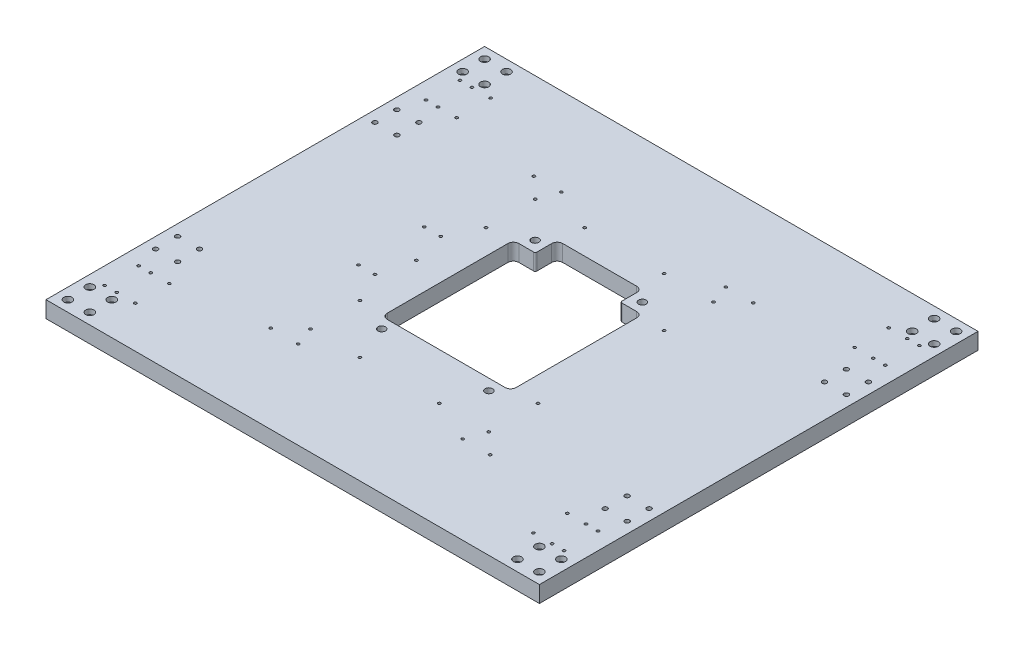
SolidWorks part; units mm, degrees
material "6061 Alloy"
ref_plane "Front Plane" through (0, 0, 0) normal (0, 0, 1) x (1, 0, 0)
ref_plane "Top Plane" through (0, 0, 0) normal (0, 1, 0) x (1, 0, 0)
ref_plane "Right Plane" through (0, 0, 0) normal (1, 0, 0) x (0, 0, -1)
sketch "Sketch2" plane through (0, 0, 0) normal (0, 1, 0) x (1, 0, 0)
  line L1 (-450, -400) -> (450, -400)
  line L2 (-450, -400) -> (-450, 400)
  line L3 (-450, 400) -> (450, 400)
  line L4 (450, -400) -> (450, 400)
  line L5 (-450, -400) -> (450, 400) construction
  line L6 (-450, 400) -> (450, -400) construction
  point P0 (0, 0)
  dimension "D1" = 800
  dimension "D2" = 900
extrude "Boss-Extrude1" add sketch "Sketch2" against normal blind 30
hole_wizard "M6 Tapped Hole1" positions "Sketch3" profile "Sketch4" tap size "M6" standard "GB"
sketch "Sketch3" plane through (0, 0, 0) normal (0, 1, 0) x (1, 0, 0)
  line L0 (-16.5, 0) -> (16.5, 0) construction
  line L1 (0, -16.5) -> (0, 16.5) construction
  line L2 (-174.35, -84) -> (-174.35, 84) construction
  point P0 (-419, 324.022)
  point P3 (-397, 324.022)
  point P6 (-363, 324.022)
  point P9 (-419, 262.022)
  point P12 (-397, 262.022)
  point P15 (-363, 262.022)
  point P27 (-200, 240)
  point P30 (-150, 240)
  point P33 (-162.5, 115)
  point P36 (-162.5, 205)
  point P39 (-72.5, 205)
  point P42 (-190.0019, 60)
  point P45 (-220.0019, 60)
  point P54 (-220.0019, -60)
  point P55 (-190.0019, -60)
  point P56 (-72.5, -205)
  point P57 (-162.5, -205)
  point P58 (-162.5, -115)
  point P59 (-150, -240)
  point P60 (-200, -240)
  point P61 (-363, -262.022)
  point P62 (-397, -262.022)
  point P63 (-419, -262.022)
  point P64 (-363, -324.022)
  point P65 (-397, -324.022)
  point P66 (-419, -324.022)
  point P69 (419, -324.022)
  point P70 (397, -324.022)
  point P71 (363, -324.022)
  point P72 (419, -262.022)
  point P73 (397, -262.022)
  point P74 (363, -262.022)
  point P75 (200, -240)
  point P76 (150, -240)
  point P77 (162.5, -115)
  point P78 (162.5, -205)
  point P79 (72.5, -205)
  point P84 (72.5, 205)
  point P85 (162.5, 205)
  point P86 (162.5, 115)
  point P87 (150, 240)
  point P88 (200, 240)
  point P89 (363, 262.022)
  point P90 (397, 262.022)
  point P91 (419, 262.022)
  point P92 (363, 324.022)
  point P93 (397, 324.022)
  point P94 (419, 324.022)
  point P95 (-174.35, 0)
cosmetic thread "Hole Thread1" parameters "D1"=20, "D2"=6
cosmetic thread "Hole Thread2" parameters "D1"=20, "D2"=6
cosmetic thread "Hole Thread3" parameters "D1"=20, "D2"=6
cosmetic thread "Hole Thread4" parameters "D1"=20, "D2"=6
cosmetic thread "Hole Thread5" parameters "D1"=20, "D2"=6
cosmetic thread "Hole Thread6" parameters "D1"=20, "D2"=6
cosmetic thread "Hole Thread7" parameters "D1"=20, "D2"=6
cosmetic thread "Hole Thread8" parameters "D1"=20, "D2"=6
cosmetic thread "Hole Thread9" parameters "D1"=20, "D2"=6
cosmetic thread "Hole Thread10" parameters "D1"=20, "D2"=6
cosmetic thread "Hole Thread11" parameters "D1"=20, "D2"=6
cosmetic thread "Hole Thread12" parameters "D1"=20, "D2"=6
cosmetic thread "Hole Thread13" parameters "D1"=20, "D2"=6
cosmetic thread "Hole Thread14" parameters "D1"=20, "D2"=6
cosmetic thread "Hole Thread15" parameters "D1"=20, "D2"=6
cosmetic thread "Hole Thread16" parameters "D1"=20, "D2"=6
cosmetic thread "Hole Thread17" parameters "D1"=20, "D2"=6
cosmetic thread "Hole Thread18" parameters "D1"=20, "D2"=6
cosmetic thread "Hole Thread19" parameters "D1"=20, "D2"=6
cosmetic thread "Hole Thread20" parameters "D1"=20, "D2"=6
cosmetic thread "Hole Thread21" parameters "D1"=20, "D2"=6
cosmetic thread "Hole Thread22" parameters "D1"=20, "D2"=6
cosmetic thread "Hole Thread23" parameters "D1"=20, "D2"=6
cosmetic thread "Hole Thread24" parameters "D1"=20, "D2"=6
cosmetic thread "Hole Thread25" parameters "D1"=20, "D2"=6
cosmetic thread "Hole Thread26" parameters "D1"=20, "D2"=6
cosmetic thread "Hole Thread27" parameters "D1"=20, "D2"=6
cosmetic thread "Hole Thread28" parameters "D1"=20, "D2"=6
cosmetic thread "Hole Thread29" parameters "D1"=20, "D2"=6
cosmetic thread "Hole Thread30" parameters "D1"=20, "D2"=6
cosmetic thread "Hole Thread31" parameters "D1"=20, "D2"=6
cosmetic thread "Hole Thread32" parameters "D1"=20, "D2"=6
cosmetic thread "Hole Thread33" parameters "D1"=20, "D2"=6
cosmetic thread "Hole Thread34" parameters "D1"=20, "D2"=6
cosmetic thread "Hole Thread35" parameters "D1"=20, "D2"=6
cosmetic thread "Hole Thread36" parameters "D1"=20, "D2"=6
cosmetic thread "Hole Thread37" parameters "D1"=20, "D2"=6
cosmetic thread "Hole Thread38" parameters "D1"=20, "D2"=6
cosmetic thread "Hole Thread39" parameters "D1"=20, "D2"=6
cosmetic thread "Hole Thread40" parameters "D1"=20, "D2"=6
cosmetic thread "Hole Thread41" parameters "D1"=20, "D2"=6
cosmetic thread "Hole Thread42" parameters "D1"=20, "D2"=6
cosmetic thread "Hole Thread43" parameters "D1"=20, "D2"=6
cosmetic thread "Hole Thread44" parameters "D1"=20, "D2"=6
cosmetic thread "Hole Thread45" parameters "D1"=20, "D2"=6
cosmetic thread "Hole Thread46" parameters "D1"=20, "D2"=6
cosmetic thread "Hole Thread47" parameters "D1"=20, "D2"=6
cosmetic thread "Hole Thread48" parameters "D1"=20, "D2"=6
sketch "Sketch4" plane through (-419, 0, -324.022) normal (1, 0, 0) x (0, 0, 1)
  line L0 (0, 0) -> (0, 21.5022)
  line L1 (0, 21.5022) -> (2.5, 20)
  line L2 (2.5, 20) -> (2.5, 0)
  line L5 (2.5, 0) -> (0, 0)
  line L10 (0, 21.5022) -> (-2.5, 20) construction
  line L11 (0, -6.35) -> (0, 107.95) construction
  dimension "Tap Drill Dia." = 5
  dimension "Tap Drill Depth" = 20
  dimension "Drill Angle" = 118
cosmetic thread "Hole Thread49" parameters "D1"=20, "D2"=6
sketch "Sketch5" plane through (0, -30, 0) normal (0, -1, 0) x (1, 0, 0)
  line L1 (77.5, -160) -> (-77.5, -160)
  line L2 (77.5, -160) -> (77.5, 120)
  line L3 (77.5, 120) -> (-77.5, 120)
  line L4 (-77.5, -160) -> (-77.5, 120)
  line L5 (77.5, -160) -> (-77.5, 120) construction
  line L6 (77.5, 120) -> (-77.5, -160) construction
  point P0 (0, 0)
  point P7 (0, -20)
  dimension "D1" = 155
  dimension "D2" = 160
  dimension "D3" = 120
extrude "Cut-Extrude1" cut sketch "Sketch5" against normal through all
sketch "Sketch6" plane through (0, -30, 0) normal (0, -1, 0) x (-1, 0, 0)
  line L0 (0, 16.5) -> (0, -16.5) construction
  line L1 (-92.5, 22.5) -> (92.5, -52.5) construction
  point P0 (92.5, -52.5)
  point P1 (92.5, 22.5)
  point P4 (-92.5, 22.5)
  point P5 (-92.5, -52.5)
  point P8 (0, -15)
  point P9 (92.5, -15)
  point P13 (-92.5, -15)
  dimension "D1" = 15
  dimension "D2" = 75
  dimension "D3" = 185
sketch "Sketch9" plane through (0, -30, 0) normal (0, -1, 0) x (-1, 0, 0)
  line L0 (-77.5, -120) -> (77.5, -120) construction
  line L1 (-117.5, 120) -> (117.5, 120)
  line L2 (-117.5, 120) -> (-117.5, -120)
  line L3 (-117.5, -120) -> (117.5, -120)
  line L4 (117.5, 120) -> (117.5, -120)
  line L5 (-117.5, 120) -> (117.5, -120) construction
  line L6 (-117.5, -120) -> (117.5, 120) construction
  line L7 (77.5, -120) -> (77.5, 160) construction
  line L8 (77.5, 160) -> (-77.5, 160) construction
  point P0 (0, 0)
  dimension "D1" = 40
  dimension "D2" = 40
extrude "Cut-Extrude2" cut sketch "Sketch9" against normal through all
fillet "Fillet2" radius 3 2 edges at (-77.5, -15, -120) (77.5, -15, -120)
hole_wizard "CBORE for M12 Hexagon socket head cap screws1" positions "Sketch14" profile "Sketch16" counterbore size "M12" standard "GB" end condition through all
sketch "Sketch14" plane through (0, -30, 0) normal (0, -1, 0) x (-1, 0, 0)
  line L0 (0, 16.5) -> (0, -16.5) construction
  line L1 (-16.5, 0) -> (16.5, 0) construction
  point P0 (-97.75, 140)
  point P5 (97.75, 140)
  point P8 (97.75, -140)
  point P9 (-97.75, -140)
  dimension "D1" = 195.5
  dimension "D2" = 280
sketch "Sketch16" plane through (97.75, -30, -140) normal (1, 0, 0) x (0, 0, -1)
  line L0 (0, 0) -> (0, 30)
  line L1 (0, 30) -> (6.75, 30)
  line L3 (6.75, 30) -> (6.75, 13)
  line L4 (6.75, 13) -> (10, 13)
  line L5 (10, 13) -> (10, 0)
  line L7 (10, 0) -> (0, 0)
  line L11 (0, -6.35) -> (0, 107.95) construction
  dimension "Thru Hole Dia." = 13.5
  dimension "Thru Hole Depth" = 30
  dimension "C'Bore Dia." = 20
  dimension "C'Bore Depth" = 13
fillet "Fillet1" radius 10 6 edges at (77.5, -15, -160) (-77.5, -15, -160) (117.5, -15, -120) (117.5, -15, 120) (-117.5, -15, 120) (-117.5, -15, -120)
hole_wizard "M12 Tapped Hole1" positions "Sketch20" profile "Sketch21" tap size "M12" standard "GB"
sketch "Sketch20" plane through (0, -30, 0) normal (0, -1, 0) x (-1, 0, 0)
  line L0 (0, 16.5) -> (0, -16.5) construction
  line L1 (-135, 20) -> (-135, -50) construction
  line L3 (135, 20) -> (135, -50) construction
  point P0 (-135, 20)
  point P2 (-135, -50)
  point P8 (135, -50)
  point P9 (135, 20)
  point P18 (-135, -15)
  point P20 (135, -15)
  dimension "D1" = 20
  dimension "D2" = 50
  dimension "D3" = 135
cosmetic thread "Hole Thread60" parameters "D1"=23.25, "D2"=12
cosmetic thread "Hole Thread61" parameters "D1"=23.25, "D2"=12
cosmetic thread "Hole Thread62" parameters "D1"=23.25, "D2"=12
cosmetic thread "Hole Thread63" parameters "D1"=23.25, "D2"=12
sketch "Sketch21" plane through (135, -30, -20) normal (1, 0, 0) x (0, 0, -1)
  line L0 (0, 0) -> (0, 28.0644)
  line L1 (0, 28.0644) -> (5.1, 25)
  line L2 (5.1, 25) -> (5.1, 0)
  line L5 (5.1, 0) -> (0, 0)
  line L10 (0, 28.0644) -> (-5.1, 25) construction
  line L11 (0, -6.35) -> (0, 107.95) construction
  dimension "Tap Drill Dia." = 10.2
  dimension "Tap Drill Depth" = 25
  dimension "Drill Angle" = 118
cosmetic thread "Hole Thread64" parameters "D1"=23.25, "D2"=12
cosmetic thread "Hole Thread65" parameters "D1"=23.25, "D2"=12
sketch "Sketch22" plane through (0, -30, 0) normal (0, -1, 0) x (1, 0, 0)
  point P0 (-390, 180)
  point P1 (-430, 180)
  point P3 (-430, 220)
  point P4 (-390, 220)
  dimension "D1" = 390
  dimension "D2" = 180
  dimension "D3" = 40
  dimension "D4" = 40
hole_wizard "CBORE for M8 Hexagon socket head cap screws1" positions "Sketch23" profile "Sketch24" counterbore size "M8" standard "GB" end condition through all
sketch "Sketch23" plane through (0, -30, 0) normal (0, -1, 0) x (-1, 0, 0)
  line L0 (-16.5, 0) -> (16.5, 0) construction
  line L1 (0, 16.5) -> (0, -16.5) construction
  point P0 (-390, 180)
  point P2 (-430, 180)
  point P4 (-430, 220)
  point P6 (-390, 220)
  point P11 (-390, -220)
  point P12 (-430, -220)
  point P13 (-430, -180)
  point P14 (-390, -180)
  point P17 (390, -180)
  point P18 (430, -180)
  point P19 (430, -220)
  point P20 (390, -220)
  point P21 (390, 220)
  point P22 (430, 220)
  point P23 (430, 180)
  point P24 (390, 180)
  dimension "D1" = 180
  dimension "D2" = 390
  dimension "D3" = 40
  dimension "D4" = 40
sketch "Sketch24" plane through (390, -30, -180) normal (1, 0, 0) x (0, 0, -1)
  line L0 (0, 0) -> (0, 30)
  line L1 (0, 30) -> (4.2, 30)
  line L3 (4.2, 30) -> (4.2, 9)
  line L4 (4.2, 9) -> (7.5, 9)
  line L5 (7.5, 9) -> (7.5, 0)
  line L7 (7.5, 0) -> (0, 0)
  line L11 (0, -6.35) -> (0, 107.95) construction
  dimension "Thru Hole Dia." = 8.4
  dimension "Thru Hole Depth" = 30
  dimension "C'Bore Dia." = 15
  dimension "C'Bore Depth" = 9
hole_wizard "CBORE for M8 Hexagon socket head cap screws2" positions "Sketch25" profile "Sketch26" counterbore size "M8" standard "GB" end condition through all
sketch "Sketch25" plane through (0, 0, 0) normal (0, 1, 0) x (1, 0, 0)
  line L0 (450, 400) -> (-450, 400) construction
  line L1 (450, -400) -> (450, 400) construction
  line L2 (-16.5, 0) -> (16.5, 0) construction
  line L3 (0, -16.5) -> (0, 16.5) construction
  point P0 (390, 380)
  point P2 (430, 380)
  point P4 (430, 340)
  point P6 (390, 340)
  point P16 (390, -340)
  point P17 (430, -340)
  point P18 (430, -380)
  point P19 (390, -380)
  point P22 (-390, -380)
  point P23 (-430, -380)
  point P24 (-430, -340)
  point P25 (-390, -340)
  point P26 (-390, 340)
  point P27 (-430, 340)
  point P28 (-430, 380)
  point P29 (-390, 380)
  dimension "D1" = 40
  dimension "D2" = 40
  dimension "D3" = 20
  dimension "D4" = 20
sketch "Sketch26" plane through (390, 0, -380) normal (1, 0, 0) x (0, 0, 1)
  line L0 (0, 0) -> (0, 30)
  line L1 (0, 30) -> (4.2, 30)
  line L3 (4.2, 30) -> (4.2, 9)
  line L4 (4.2, 9) -> (7.5, 9)
  line L5 (7.5, 9) -> (7.5, 0)
  line L7 (7.5, 0) -> (0, 0)
  line L11 (0, -6.35) -> (0, 107.95) construction
  dimension "Thru Hole Dia." = 8.4
  dimension "Thru Hole Depth" = 30
  dimension "C'Bore Dia." = 15
  dimension "C'Bore Depth" = 9
